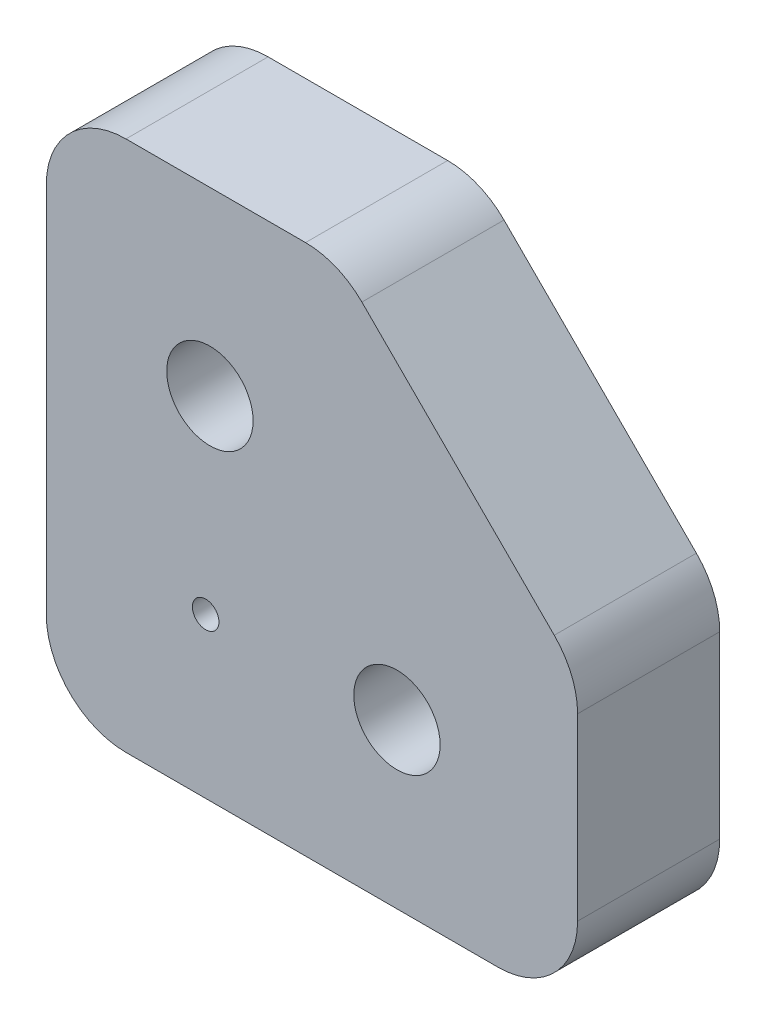
SolidWorks part; units mm, degrees
ref_plane "Front Plane" through (0, 0, 0) normal (0, 0, 1) x (1, 0, 0)
ref_plane "Top Plane" through (0, 0, 0) normal (0, 1, 0) x (1, 0, 0)
ref_plane "Right Plane" through (0, 0, 0) normal (1, 0, 0) x (0, 0, -1)
sketch "Model" plane through (0, 0, 0) normal (0, 0, 1) x (1, 0, 0)
  line L0 (1.8805, 19.1213) -> (9.1213, 11.8805)
  line L1 (-7, 0) -> (7, 0)
  line L2 (-10, 3) -> (-10, 17)
  line L3 (-7, 20) -> (-0.2408, 20)
  line L4 (10, 3) -> (10, 9.7592)
  arc A0 (-10, 3) -> (-7, 0) centre (-7, 3) ccw
  arc A1 (7, 0) -> (10, 3) centre (7, 3) ccw
  arc A2 (-7, 20) -> (-10, 17) centre (-7, 17) ccw
  arc A3 (10, 9.7592) -> (9.1213, 11.8805) centre (7, 9.7592) ccw
  arc A4 (1.8805, 19.1213) -> (-0.2408, 20) centre (-0.2408, 17) ccw
  circle A5 centre (-4, 6) radius 0.5
  circle A6 centre (-3.84, 13.2) radius 1.2
  circle A7 centre (-3.84, 13.2) radius 1.625
  circle A8 centre (3.2, 6.16) radius 1.2
  circle A9 centre (3.2, 6.16) radius 1.625
  dimension "D4" = 3
  dimension "D14" = 1
  dimension "D16" = 6
  dimension "D18" = 6
  dimension "D20" = 2.4
  dimension "D22" = 0.425
  dimension "D8" = 20
  dimension "D9" = 20
  dimension "D12" = 135
  dimension "D24" = 13.2
  dimension "D26" = 6.16
  dimension "D30" = 6.16
  dimension "D32" = 13.2
  dimension "D34" = 10.24
extrude "Boss-Extrude1" add sketch "Model" along normal blind 5.35 contours L0 A4 L3 A2 L2 A0 L1 A1 L4 A3 A9 A7 A5
equation "\"mdfthick\"=5.35"
equation "\"D1@Boss-Extrude1\"=\"mdfthick\""
